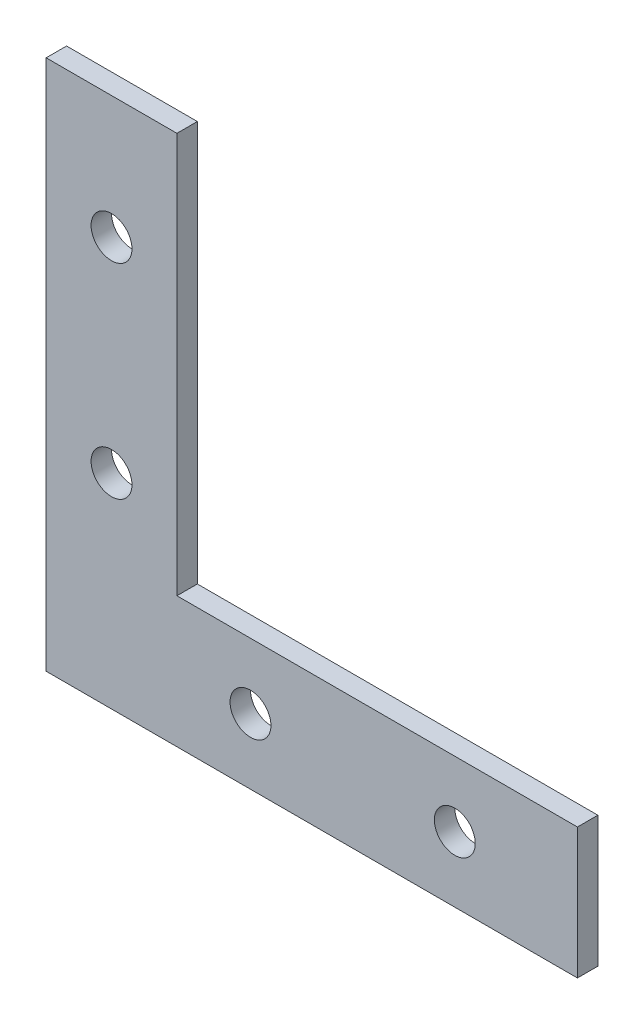
SolidWorks part; units mm, degrees
ref_plane "Front Plane" through (0, 0, 0) normal (0, 0, 1) x (1, 0, 0)
ref_plane "Top Plane" through (0, 0, 0) normal (0, 1, 0) x (1, 0, 0)
ref_plane "Right Plane" through (0, 0, 0) normal (1, 0, 0) x (0, 0, -1)
sketch "Sketch1" plane through (0, 0, 0) normal (0, 0, 1) x (1, 0, 0)
  line L0 (0, 0) -> (65, 0)
  line L2 (16, 16) -> (16, 65)
  line L3 (16, 65) -> (0, 65)
  line L4 (0, 0) -> (0, 65)
  line L7 (16, 16) -> (65, 16)
  line L8 (65, 0) -> (65, 16)
  line L9 (0, 0) -> (16, 16) construction
  line L10 (8, 8) -> (65, 8) construction
  circle A0 centre (25, 8) radius 2.5
  circle A1 centre (50, 8) radius 2.5
  circle A2 centre (8, 50) radius 2.5
  circle A3 centre (8, 25) radius 2.5
  dimension "D5" = 5
  dimension "D6" = 5
  dimension "D7" = 25
  dimension "D1" = 16
  dimension "D2" = 65
  dimension "D3" = 65
  dimension "D4" = 16
  dimension "D8" = 15
extrude "Boss-Extrude1" add sketch "Sketch1" along normal mid plane 2.5
